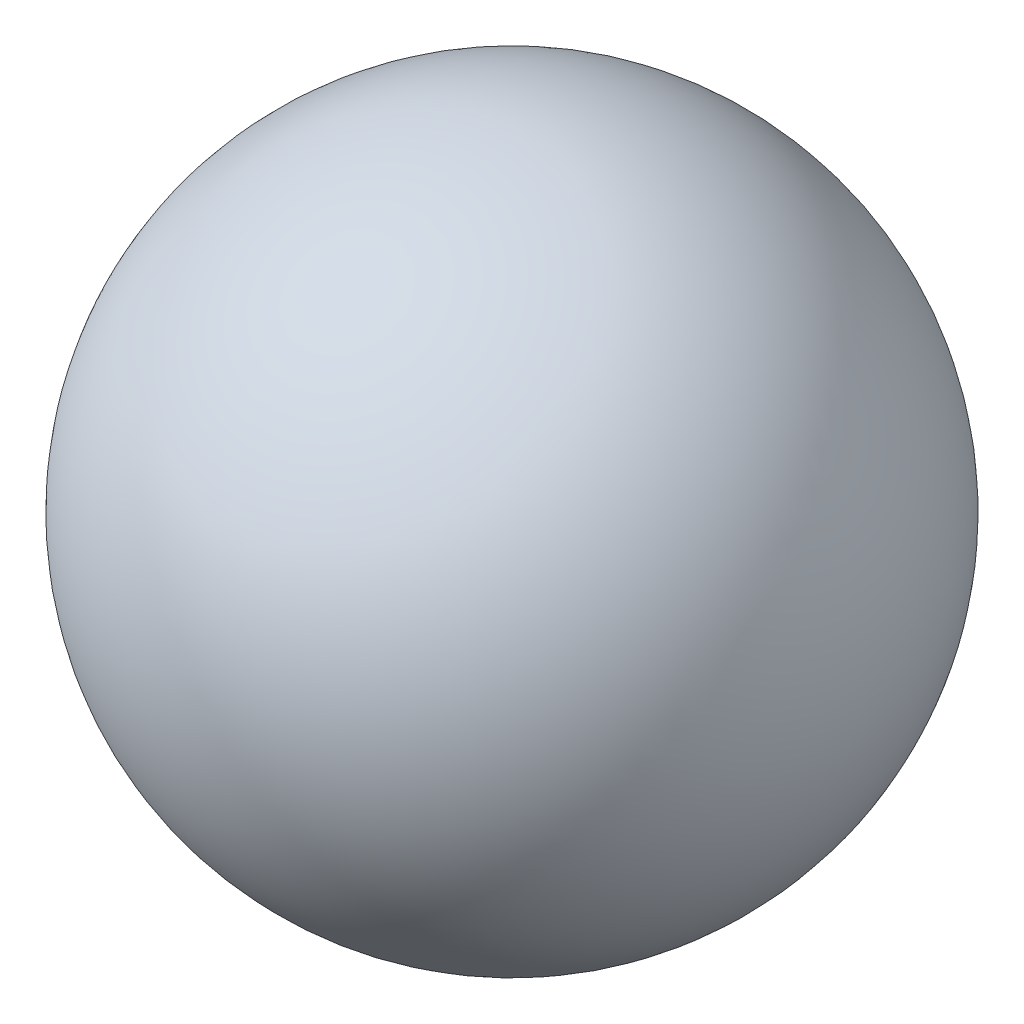
SolidWorks part; units mm, degrees
material "ABS"
ref_plane "Front Plane" through (0, 0, 0) normal (0, 0, 1) x (1, 0, 0)
ref_plane "Top Plane" through (0, 0, 0) normal (0, 1, 0) x (1, 0, 0)
ref_plane "Right Plane" through (0, 0, 0) normal (1, 0, 0) x (0, 0, -1)
sketch "Sphere Profile" plane through (0, 0, 0) normal (0, 0, 1) x (1, 0, 0)
  line L0 (0, 1.35) -> (0, -1.35)
  arc A0 (0, 1.35) -> (0, -1.35) centre (0, 0) ccw
  dimension "D1" = 2.7
revolve "Sphere Revolve" add sketch "Sphere Profile" angle 360 about L0
sketch "Spring Slot Profile" plane through (0, 0, 0) normal (1, 0, 0) x (0, 0, -1)
  circle A0 centre (0, 0) radius 0.5
  dimension "D1" = 1
extrude "Spring Slot Cut" cut sketch "Spring Slot Profile" against normal blind 10
